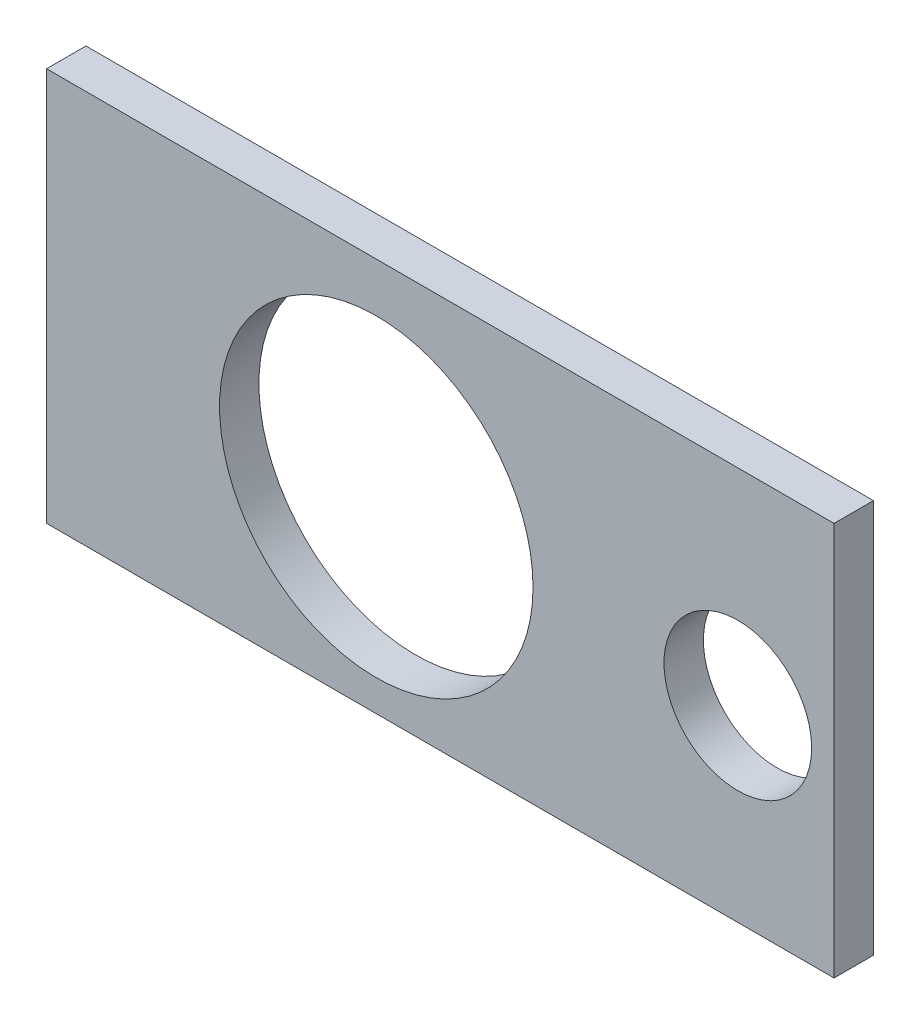
SolidWorks part; units mm, degrees
ref_plane "Front Plane" through (0, 0, 0) normal (0, 0, 1) x (1, 0, 0)
ref_plane "Top Plane" through (0, 0, 0) normal (0, 1, 0) x (1, 0, 0)
ref_plane "Right Plane" through (0, 0, 0) normal (1, 0, 0) x (0, 0, -1)
sketch "Sketch1" plane through (0, 0, 0) normal (0, 0, 1) x (1, 0, 0)
  line L1 (-31.0261, 13.2792) -> (19.7739, 13.2792)
  line L2 (-31.0261, 13.2792) -> (-31.0261, -12.1208)
  line L3 (-31.0261, -12.1208) -> (19.7739, -12.1208)
  line L4 (19.7739, 13.2792) -> (19.7739, -12.1208)
  line L5 (19.7739, 13.2792) -> (7.0739, 13.2792)
  line L6 (19.7739, 13.2792) -> (19.7739, -12.1208)
  line L7 (19.7739, -12.1208) -> (7.0739, -12.1208)
  circle A0 centre (13.5668, 0) radius 4.7625
  circle A1 centre (-9.7558, 0) radius 10.1113
  dimension "D4" = 9.525
  dimension "D1" = 50.8
  dimension "D2" = 25.4
  dimension "D3" = 12.7
extrude "Boss-Extrude1" add sketch "Sketch1" against normal blind 2.54 contours L4 L1 L2 L3 A1 A0
